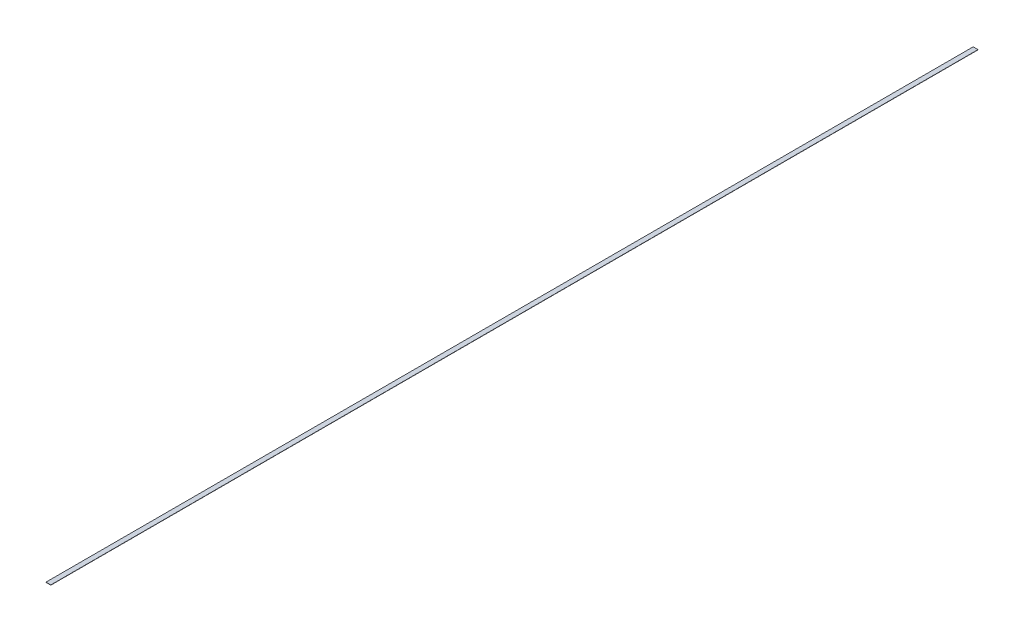
SolidWorks part; units mm, degrees
ref_plane "Front Plane" through (0, 0, 0) normal (0, 0, 1) x (1, 0, 0)
ref_plane "Top Plane" through (0, 0, 0) normal (0, 1, 0) x (1, 0, 0)
ref_plane "Right Plane" through (0, 0, 0) normal (1, 0, 0) x (0, 0, -1)
sketch "Sketch2" plane through (0, 0, 0) normal (0, 1, 0) x (1, 0, 0)
  line L1 (-25.4, 4876.8) -> (25.4, 4876.8)
  line L2 (-25.4, 4876.8) -> (-25.4, -4876.8)
  line L3 (-25.4, -4876.8) -> (25.4, -4876.8)
  line L4 (25.4, 4876.8) -> (25.4, -4876.8)
  line L5 (-25.4, 4876.8) -> (25.4, -4876.8) construction
  line L6 (-25.4, -4876.8) -> (25.4, 4876.8) construction
  point P0 (0, 0)
  dimension "D1" = 50.8
  dimension "D2" = 9753.6
extrude "Boss-Extrude1" add sketch "Sketch2" along normal blind 2.54
